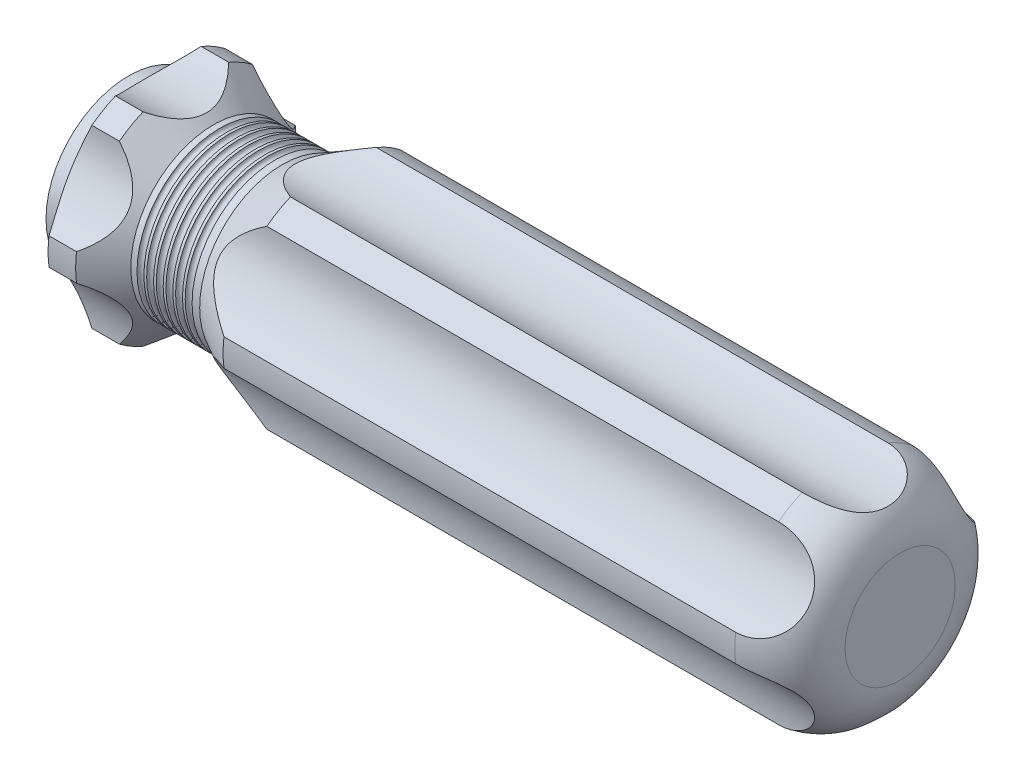
SolidWorks part; units mm, degrees
ref_plane "Front Plane" through (0, 0, 0) normal (0, 0, 1) x (1, 0, 0)
ref_plane "Top Plane" through (0, 0, 0) normal (0, 1, 0) x (1, 0, 0)
ref_plane "Right Plane" through (0, 0, 0) normal (1, 0, 0) x (0, 0, -1)
sketch "Sketch1" plane through (0, 0, 0) normal (0, 0, 1) x (1, 0, 0)
  line L0 (0, 6) -> (1, 6)
  line L1 (0, 0) -> (56, 0)
  line L2 (0, 0) -> (0, 8) construction
  line L3 (0, 8) -> (56, 8) construction
  line L4 (56, 0) -> (56, 4)
  line L5 (1, 6) -> (2.1547, 8)
  line L6 (2.1547, 8) -> (4.1547, 8)
  line L7 (4.1547, 8) -> (6.1547, 6)
  line L8 (6.1547, 6) -> (11.1547, 6)
  line L9 (11.1547, 6) -> (14.8552, 8)
  line L10 (14.8552, 8) -> (52, 8)
  line L11 (0, 6) -> (0, 0)
  arc A0 (56, 4) -> (52, 8) centre (52, 4) ccw
  dimension "D10" = 4
  dimension "D1" = 56
  dimension "D2" = 8
  dimension "D3" = 1
  dimension "D4" = 120
  dimension "D5" = 2
  dimension "D6" = 2
  dimension "D7" = 28.39
  dimension "D8" = 5
  dimension "D9" = 135
revolve "Revolve1" add sketch "Sketch1" angle 360 about L1
sketch "Sketch4" plane through (0, 0, 0) normal (0, 0, 1) x (1, 0, 0)
  line L0 (11.1547, 6) -> (6.1547, 6) construction
  line L1 (0, 0) -> (23.1244, 0) construction
  line L2 (6.1547, 6) -> (6.1547, -6) construction
  line L3 (0.7, 0) -> (23.8244, 0) construction
  line L4 (1.4, 0) -> (24.5244, 0) construction
  line L5 (2.1, 0) -> (25.2244, 0) construction
  line L6 (2.8, 0) -> (25.9244, 0) construction
  line L7 (3.5, 0) -> (26.6244, 0) construction
  circle A0 centre (6.8547, 6) radius 0.25
  circle A1 centre (7.5547, 6) radius 0.25
  circle A2 centre (8.2547, 6) radius 0.25
  circle A3 centre (8.9547, 6) radius 0.25
  circle A4 centre (9.6547, 6) radius 0.25
  circle A5 centre (10.3547, 6) radius 0.25
  dimension "D1" = 0.5
  dimension "D2" = 0.7
  dimension "D3" = 6
revolve "Cut-Revolve2" cut sketch "Sketch4" angle 360 about L1
sketch "Sketch5" plane through (0, 0, 0) normal (-1, 0, 0) x (0, 0, 1)
  circle A0 centre (0, 12.5) radius 6
  dimension "D2" = 12
  dimension "D1" = 12.5
extrude "Cut-Extrude1" cut sketch "Sketch5" against normal through all
pattern_circular "CirPattern1" count 6 over 360 about axis through (0, 0, 0) along (1, 0, 0) of "Cut-Extrude1"
sketch "Sketch6" plane through (0, 0, 0) normal (0, 1, 0) x (1, 0, 0)
  line L0 (0, 0) -> (56.6884, 0) construction
  text T0 "     Imran's Handle" font "Century Gothic" height in points 8
extrude "Cut-Extrude2" cut sketch "Sketch6" against normal blind 1
sketch "Sketch7" plane through (0, 0, 0) normal (-1, 0, 0) x (0, 0, 1)
  circle A0 centre (0, 0) radius 1.5
  dimension "D1" = 3
extrude "Cut-Extrude3" cut sketch "Sketch7" against normal blind 30
